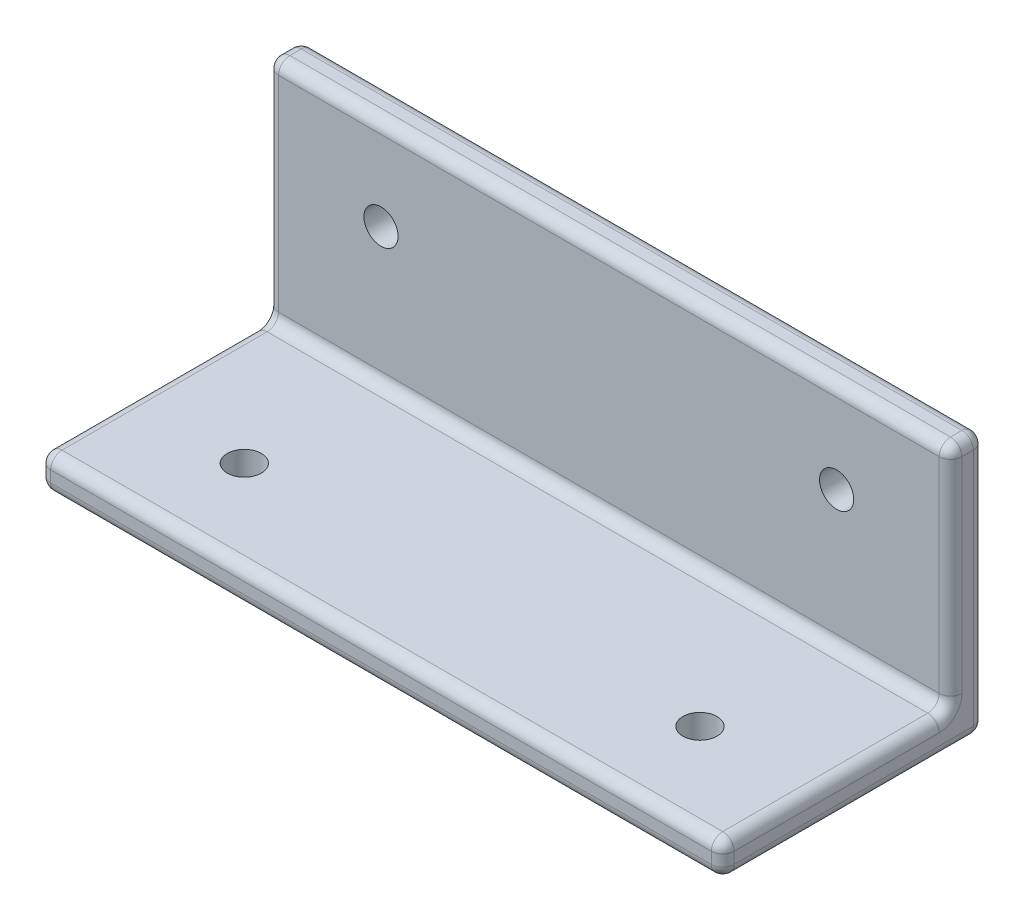
SolidWorks part; units mm, degrees
ref_plane "Front Plane" through (0, 0, 0) normal (0, 0, 1) x (1, 0, 0)
ref_plane "Top Plane" through (0, 0, 0) normal (0, 1, 0) x (1, 0, 0)
ref_plane "Right Plane" through (0, 0, 0) normal (1, 0, 0) x (0, 0, -1)
sketch "Sketch1" plane through (0, 0, 0) normal (0, 1, 0) x (1, 0, 0)
  line L2 (-30, 10) -> (-30, -10)
  line L3 (-30, -10) -> (30, -10)
  line L4 (30, 10) -> (30, -10)
  line L5 (-30, 10) -> (30, -10) construction
  line L6 (-30, -10) -> (30, 10) construction
  line L9 (-30, 10) -> (30, 10)
  point P0 (0, 0)
extrude "Boss-Extrude1" add sketch "Sketch1" along normal blind 3 contours L2 L3 L4 L9
sketch "Sketch3" plane through (0, 0, 0) normal (0, 1, 0) x (1, 0, 0)
  line L1 (-30, 13) -> (30, 13)
  line L2 (-30, 13) -> (-30, 10)
  line L3 (-30, 10) -> (30, 10)
  line L4 (30, 13) -> (30, 10)
  line L5 (-30, 13) -> (30, 10) construction
  line L6 (-30, 10) -> (30, 13) construction
  point P0 (0, 11.5)
extrude "Boss-Extrude2" add sketch "Sketch3" along normal blind 23
sketch "Sketch4" plane through (0, 3, 0) normal (0, 1, 0) x (1, 0, 0)
  line L1 (0, 10) -> (0, -10) construction
  line L2 (-30, 10) -> (30, 10) construction
  line L3 (-30, -10) -> (30, -10) construction
  circle A1 centre (-20, -2) radius 1.5
  circle A2 centre (20, -2) radius 1.5
  dimension "D1" = 12
  dimension "D2" = 20
fillet "Fillet2" radius 1 18 edges at (0, 0, -13) (30, 23, -11.5) (0, 3, -10) (-30, 23, -11.5) (0, 23, -10) (0, 23, -13) (-30, 11.5, -13) (-30, 13, -10) (-30, 0, -1.5) (-30, 1.5, 10) (0, 3, 10) (0, 0, 10) (30, 0, -1.5) (30, 11.5, -13) (30, 13, -10) (30, 3, 0) (-30, 3, 0) (30, 1.5, 10)
extrude "Cut-Extrude1" cut sketch "Sketch4" against normal through all contours A1 | A2
sketch "Sketch6" plane through (0, 0, -10) normal (0, 0, 1) x (1, 0, 0)
  line L0 (0, 22) -> (0, 4) construction
  line L1 (29, 22) -> (-29, 22) construction
  line L2 (-29, 4) -> (29, 4) construction
  line L3 (29, 3) -> (-29, 3) construction
  circle A0 centre (-20, 15) radius 1.5
  circle A1 centre (20, 15) radius 1.5
  dimension "D1" = 12
  dimension "D2" = 20
extrude "Cut-Extrude2" cut sketch "Sketch6" against normal through all contours A0 | A1
